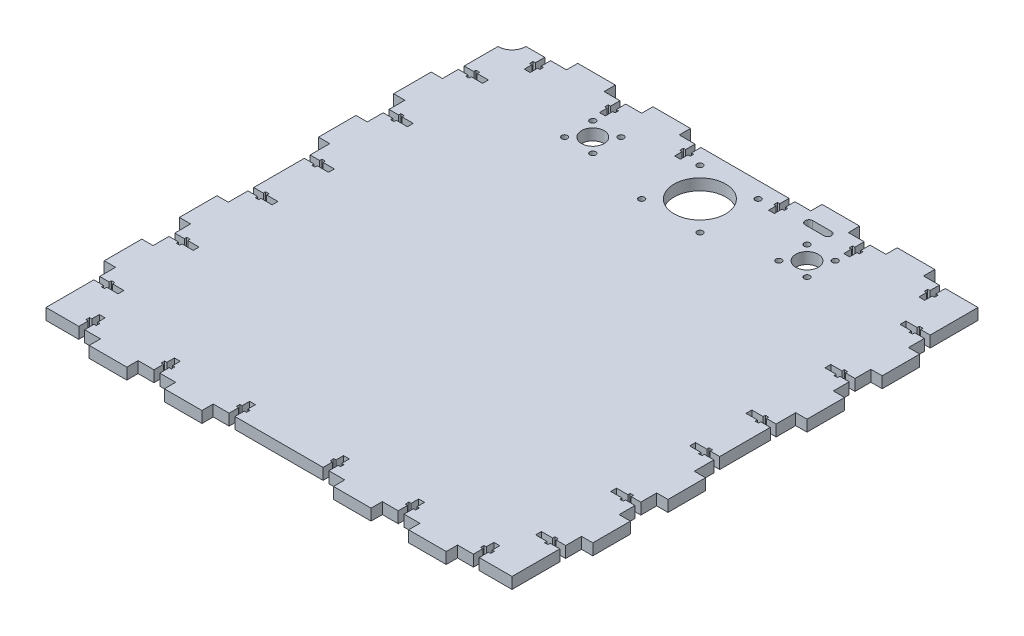
SolidWorks part; units mm, degrees
ref_plane "Front Plane" through (0, 0, 0) normal (0, 0, 1) x (1, 0, 0)
ref_plane "Top Plane" through (0, 0, 0) normal (0, 1, 0) x (1, 0, 0)
ref_plane "Right Plane" through (0, 0, 0) normal (1, 0, 0) x (0, 0, -1)
sketch "Sketch1" plane through (0, 0, 0) normal (0, 1, 0) x (1, 0, 0)
  line L0 (130, 260) -> (130, 0) construction
  line L1 (0, 0) -> (260, 0)
  line L2 (0, 0) -> (0, 260)
  line L3 (0, 260) -> (260, 260)
  line L4 (260, 0) -> (260, 260)
  line L5 (0, 260) -> (260, 260)
  line L6 (0, 260) -> (0, 254)
  line L7 (0, 254) -> (260, 254)
  line L8 (260, 260) -> (260, 254)
  line L9 (35, 260) -> (55, 260)
  line L10 (35, 260) -> (35, 254)
  line L11 (35, 254) -> (55, 254)
  line L12 (55, 260) -> (55, 254)
  line L13 (75, 254) -> (95, 254)
  line L14 (75, 254) -> (75, 260)
  line L15 (75, 260) -> (95, 260)
  line L16 (95, 254) -> (95, 260)
  line L17 (0, 130) -> (260, 130) construction
  line L18 (73, 230) -> (177.06, 230) construction
  line L19 (0, 260) -> (6, 260)
  line L20 (0, 260) -> (0, 0)
  line L21 (0, 0) -> (6, 0)
  line L22 (6, 260) -> (6, 0)
  line L23 (0, 217) -> (6, 217)
  line L24 (0, 217) -> (0, 197)
  line L25 (0, 197) -> (6, 197)
  line L26 (6, 217) -> (6, 197)
  line L27 (6, 177) -> (0, 177)
  line L28 (6, 177) -> (6, 157)
  line L29 (6, 157) -> (0, 157)
  line L30 (0, 177) -> (0, 157)
  line L31 (185, 260) -> (165, 260)
  line L32 (130, 214.5) -> (114.5, 214.5) construction
  line L34 (130, 245.5) -> (114.5, 245.5) construction
  line L35 (114.5, 214.5) -> (114.5, 245.5) construction
  line L36 (130, 230) -> (114.5, 245.5) construction
  line L37 (130, 230) -> (114.5, 214.5) construction
  line L38 (80.5, 222.5) -> (65.5, 222.5) construction
  line L39 (80.5, 222.5) -> (80.5, 237.5) construction
  line L40 (80.5, 237.5) -> (65.5, 237.5) construction
  line L41 (65.5, 222.5) -> (65.5, 237.5) construction
  line L42 (80.5, 222.5) -> (65.5, 237.5) construction
  line L43 (80.5, 237.5) -> (65.5, 222.5) construction
  line L44 (165, 254) -> (165, 260)
  line L45 (185, 254) -> (165, 254)
  line L46 (185, 254) -> (185, 260)
  line L47 (225, 254) -> (205, 254)
  line L48 (205, 260) -> (205, 254)
  line L49 (225, 260) -> (205, 260)
  line L50 (225, 260) -> (225, 254)
  line L51 (254, 157) -> (260, 157)
  line L52 (260, 177) -> (260, 157)
  line L53 (254, 177) -> (260, 177)
  line L54 (254, 177) -> (254, 157)
  line L55 (260, 197) -> (254, 197)
  line L56 (254, 217) -> (254, 197)
  line L57 (260, 217) -> (254, 217)
  line L58 (260, 217) -> (260, 197)
  line L59 (254, 83) -> (254, 103)
  line L60 (254, 83) -> (260, 83)
  line L61 (260, 83) -> (260, 103)
  line L62 (254, 103) -> (260, 103)
  line L63 (260, 43) -> (260, 63)
  line L64 (260, 43) -> (254, 43)
  line L65 (254, 43) -> (254, 63)
  line L66 (260, 63) -> (254, 63)
  line L67 (225, 0) -> (225, 6)
  line L68 (225, 0) -> (205, 0)
  line L69 (205, 0) -> (205, 6)
  line L70 (225, 6) -> (205, 6)
  line L71 (185, 6) -> (185, 0)
  line L72 (185, 6) -> (165, 6)
  line L73 (165, 6) -> (165, 0)
  line L74 (185, 0) -> (165, 0)
  line L75 (75, 0) -> (95, 0)
  line L76 (95, 6) -> (95, 0)
  line L77 (75, 6) -> (95, 6)
  line L78 (75, 6) -> (75, 0)
  line L79 (35, 6) -> (55, 6)
  line L80 (55, 0) -> (55, 6)
  line L81 (35, 0) -> (55, 0)
  line L82 (35, 0) -> (35, 6)
  line L83 (0, 63) -> (6, 63)
  line L84 (6, 43) -> (6, 63)
  line L85 (0, 43) -> (6, 43)
  line L86 (0, 43) -> (0, 63)
  line L87 (6, 103) -> (0, 103)
  line L88 (0, 83) -> (0, 103)
  line L89 (6, 83) -> (0, 83)
  line L90 (6, 83) -> (6, 103)
  line L91 (254, 260) -> (254, 0)
  line L92 (0, 6) -> (254, 6)
  circle A0 centre (73, 230) radius 6
  circle A1 centre (130, 230) radius 13.75
  circle A2 centre (65.5, 237.5) radius 1.55
  circle A3 centre (80.5, 237.5) radius 1.55
  circle A4 centre (80.5, 222.5) radius 1.55
  circle A5 centre (65.5, 222.5) radius 1.55
  circle A6 centre (114.5, 245.5) radius 1.55
  circle A7 centre (114.5, 214.5) radius 1.55
  circle A8 centre (145.5, 214.5) radius 1.55
  circle A9 centre (145.5, 245.5) radius 1.55
  circle A12 centre (187, 230) radius 6
  circle A15 centre (194.5, 237.5) radius 1.55
  circle A16 centre (194.5, 222.5) radius 1.55
  circle A17 centre (179.5, 222.5) radius 1.55
  circle A18 centre (179.5, 237.5) radius 1.55
  point P29 (3, 217)
  point P30 (3, 157)
  point P31 (3, 177)
  dimension "D13" = 12
  dimension "D14" = 27.5
  dimension "D16" = 15.5
  dimension "D22" = 3.1
  dimension "D25" = 15
  dimension "D26" = 15
  dimension "D27" = 10.6066
  dimension "D28" = 3.1
  dimension "D1" = 260
  dimension "D2" = 260
  dimension "D3" = 6
  dimension "D4" = 20
  dimension "D5" = 20
  dimension "D6" = 20
  dimension "D7" = 29
  dimension "D8" = 6
  dimension "D9" = 20
  dimension "D10" = 20
  dimension "D11" = 20
  dimension "D12" = 37
  dimension "D15" = 31
  dimension "D18" = 24
  dimension "D19" = 57
  dimension "D20" = 15
  dimension "D21" = 15
  dimension "D23" = 2
  dimension "D24" = 2
extrude "Boss-Extrude1" add sketch "Sketch1" along normal blind 6
sketch "Sketch2" plane through (0, 6, 0) normal (0, 1, 0) x (1, 0, 0)
  line L0 (6, 254) -> (35, 254) construction
  line L1 (23.45, 254) -> (26.55, 254)
  line L2 (23.45, 254) -> (23.45, 249)
  line L3 (23.45, 243.1) -> (26.55, 243.1)
  line L4 (26.55, 254) -> (26.55, 249)
  line L5 (103.45, 254) -> (106.55, 254)
  line L6 (26.55, 249) -> (27.75, 249)
  line L7 (22.25, 247.1) -> (23.45, 247.1)
  line L8 (22.25, 247.1) -> (22.25, 249)
  line L9 (22.25, 249) -> (23.45, 249)
  line L10 (27.75, 247.1) -> (27.75, 249)
  line L11 (23.45, 247.1) -> (23.45, 243.1)
  line L12 (26.55, 247.1) -> (27.75, 247.1)
  line L13 (26.55, 247.1) -> (26.55, 243.1)
  line L14 (45, 260) -> (45, 264.9812) construction
  line L15 (35, 260) -> (55, 260) construction
  line L28 (103.45, 254) -> (103.45, 249)
  line L29 (103.45, 243.1) -> (106.55, 243.1)
  line L30 (25, 243.1) -> (25, 260.914) construction
  line L31 (65, 243.1) -> (65, 260.914) construction
  line L32 (63.45, 247.1) -> (63.45, 243.1)
  line L33 (63.45, 247.1) -> (62.25, 247.1)
  line L34 (66.55, 247.1) -> (66.55, 243.1)
  line L35 (62.25, 247.1) -> (62.25, 249)
  line L36 (67.75, 249) -> (66.55, 249)
  line L37 (67.75, 247.1) -> (67.75, 249)
  line L38 (67.75, 247.1) -> (66.55, 247.1)
  line L39 (63.45, 249) -> (62.25, 249)
  line L40 (63.45, 254) -> (63.45, 249)
  line L41 (66.55, 243.1) -> (63.45, 243.1)
  line L42 (66.55, 254) -> (66.55, 249)
  line L43 (66.55, 254) -> (63.45, 254)
  line L44 (85, 260) -> (85, 268.4526) construction
  line L45 (75, 260) -> (95, 260) construction
  line L46 (106.55, 254) -> (106.55, 249)
  line L47 (106.55, 249) -> (107.75, 249)
  line L48 (102.25, 247.1) -> (103.45, 247.1)
  line L49 (102.25, 247.1) -> (102.25, 249)
  line L50 (102.25, 249) -> (103.45, 249)
  line L51 (107.75, 247.1) -> (107.75, 249)
  line L52 (103.45, 247.1) -> (103.45, 243.1)
  line L53 (106.55, 247.1) -> (107.75, 247.1)
  line L54 (106.55, 247.1) -> (106.55, 243.1)
  line L55 (130, 254) -> (130, 268.4526) construction
  line L56 (95, 254) -> (165, 254) construction
  line L62 (175, 260) -> (175, 268.4526) construction
  line L78 (195, 243.1) -> (195, 260.914) construction
  line L87 (235, 243.1) -> (235, 260.914) construction
  line L89 (215, 260) -> (215, 264.9812) construction
  line L98 (153.45, 247.1) -> (153.45, 243.1)
  line L99 (153.45, 247.1) -> (152.25, 247.1)
  line L100 (156.55, 247.1) -> (156.55, 243.1)
  line L101 (152.25, 247.1) -> (152.25, 249)
  line L102 (157.75, 249) -> (156.55, 249)
  line L103 (157.75, 247.1) -> (157.75, 249)
  line L104 (157.75, 247.1) -> (156.55, 247.1)
  line L105 (153.45, 249) -> (152.25, 249)
  line L106 (153.45, 254) -> (153.45, 249)
  line L107 (193.45, 254) -> (196.55, 254)
  line L108 (193.45, 254) -> (193.45, 249)
  line L109 (193.45, 243.1) -> (196.55, 243.1)
  line L110 (196.55, 254) -> (196.55, 249)
  line L111 (196.55, 249) -> (197.75, 249)
  line L112 (192.25, 247.1) -> (193.45, 247.1)
  line L113 (192.25, 247.1) -> (192.25, 249)
  line L114 (192.25, 249) -> (193.45, 249)
  line L115 (197.75, 247.1) -> (197.75, 249)
  line L116 (193.45, 247.1) -> (193.45, 243.1)
  line L117 (196.55, 247.1) -> (197.75, 247.1)
  line L118 (196.55, 247.1) -> (196.55, 243.1)
  line L119 (156.55, 243.1) -> (153.45, 243.1)
  line L120 (156.55, 254) -> (156.55, 249)
  line L121 (233.45, 247.1) -> (233.45, 243.1)
  line L122 (233.45, 247.1) -> (232.25, 247.1)
  line L123 (236.55, 247.1) -> (236.55, 243.1)
  line L124 (232.25, 247.1) -> (232.25, 249)
  line L125 (237.75, 249) -> (236.55, 249)
  line L126 (237.75, 247.1) -> (237.75, 249)
  line L127 (237.75, 247.1) -> (236.55, 247.1)
  line L128 (233.45, 249) -> (232.25, 249)
  line L129 (156.55, 254) -> (153.45, 254)
  line L130 (233.45, 254) -> (233.45, 249)
  line L131 (236.55, 243.1) -> (233.45, 243.1)
  line L132 (236.55, 254) -> (236.55, 249)
  line L133 (236.55, 254) -> (233.45, 254)
  line L134 (6, 130) -> (-18.5109, 130) construction
  line L135 (6, 157) -> (6, 103) construction
  line L136 (215, 0) -> (215, -4.9812) construction
  line L137 (235, 16.9) -> (235, -0.914) construction
  line L138 (195, 16.9) -> (195, -0.914) construction
  line L139 (175, 0) -> (175, -8.4526) construction
  line L140 (130, 6) -> (130, -8.4526) construction
  line L141 (85, 0) -> (85, -8.4526) construction
  line L142 (65, 16.9) -> (65, -0.914) construction
  line L143 (25, 16.9) -> (25, -0.914) construction
  line L144 (45, 0) -> (45, -4.9812) construction
  line L145 (236.55, 6) -> (233.45, 6)
  line L146 (236.55, 6) -> (236.55, 11)
  line L147 (236.55, 16.9) -> (233.45, 16.9)
  line L148 (233.45, 6) -> (233.45, 11)
  line L149 (156.55, 6) -> (153.45, 6)
  line L150 (233.45, 11) -> (232.25, 11)
  line L151 (237.75, 12.9) -> (236.55, 12.9)
  line L152 (237.75, 12.9) -> (237.75, 11)
  line L153 (237.75, 11) -> (236.55, 11)
  line L154 (232.25, 12.9) -> (232.25, 11)
  line L155 (236.55, 12.9) -> (236.55, 16.9)
  line L156 (233.45, 12.9) -> (232.25, 12.9)
  line L157 (233.45, 12.9) -> (233.45, 16.9)
  line L158 (156.55, 6) -> (156.55, 11)
  line L159 (156.55, 16.9) -> (153.45, 16.9)
  line L160 (196.55, 12.9) -> (196.55, 16.9)
  line L161 (196.55, 12.9) -> (197.75, 12.9)
  line L162 (193.45, 12.9) -> (193.45, 16.9)
  line L163 (197.75, 12.9) -> (197.75, 11)
  line L164 (192.25, 11) -> (193.45, 11)
  line L165 (192.25, 12.9) -> (192.25, 11)
  line L166 (192.25, 12.9) -> (193.45, 12.9)
  line L167 (196.55, 11) -> (197.75, 11)
  line L168 (196.55, 6) -> (196.55, 11)
  line L169 (193.45, 16.9) -> (196.55, 16.9)
  line L170 (193.45, 6) -> (193.45, 11)
  line L171 (193.45, 6) -> (196.55, 6)
  line L172 (153.45, 6) -> (153.45, 11)
  line L173 (153.45, 11) -> (152.25, 11)
  line L174 (157.75, 12.9) -> (156.55, 12.9)
  line L175 (157.75, 12.9) -> (157.75, 11)
  line L176 (157.75, 11) -> (156.55, 11)
  line L177 (152.25, 12.9) -> (152.25, 11)
  line L178 (156.55, 12.9) -> (156.55, 16.9)
  line L179 (153.45, 12.9) -> (152.25, 12.9)
  line L180 (153.45, 12.9) -> (153.45, 16.9)
  line L181 (106.55, 12.9) -> (106.55, 16.9)
  line L182 (106.55, 12.9) -> (107.75, 12.9)
  line L183 (103.45, 12.9) -> (103.45, 16.9)
  line L184 (107.75, 12.9) -> (107.75, 11)
  line L185 (102.25, 11) -> (103.45, 11)
  line L186 (102.25, 12.9) -> (102.25, 11)
  line L187 (102.25, 12.9) -> (103.45, 12.9)
  line L188 (106.55, 11) -> (107.75, 11)
  line L189 (106.55, 6) -> (106.55, 11)
  line L190 (66.55, 6) -> (63.45, 6)
  line L191 (66.55, 6) -> (66.55, 11)
  line L192 (66.55, 16.9) -> (63.45, 16.9)
  line L193 (63.45, 6) -> (63.45, 11)
  line L194 (63.45, 11) -> (62.25, 11)
  line L195 (67.75, 12.9) -> (66.55, 12.9)
  line L196 (67.75, 12.9) -> (67.75, 11)
  line L197 (67.75, 11) -> (66.55, 11)
  line L198 (62.25, 12.9) -> (62.25, 11)
  line L199 (66.55, 12.9) -> (66.55, 16.9)
  line L200 (63.45, 12.9) -> (62.25, 12.9)
  line L201 (63.45, 12.9) -> (63.45, 16.9)
  line L202 (103.45, 16.9) -> (106.55, 16.9)
  line L203 (103.45, 6) -> (103.45, 11)
  line L204 (26.55, 12.9) -> (26.55, 16.9)
  line L205 (26.55, 12.9) -> (27.75, 12.9)
  line L206 (23.45, 12.9) -> (23.45, 16.9)
  line L207 (27.75, 12.9) -> (27.75, 11)
  line L208 (22.25, 11) -> (23.45, 11)
  line L209 (22.25, 12.9) -> (22.25, 11)
  line L210 (22.25, 12.9) -> (23.45, 12.9)
  line L211 (26.55, 11) -> (27.75, 11)
  line L212 (103.45, 6) -> (106.55, 6)
  line L213 (26.55, 6) -> (26.55, 11)
  line L214 (23.45, 16.9) -> (26.55, 16.9)
  line L215 (23.45, 6) -> (23.45, 11)
  line L216 (23.45, 6) -> (26.55, 6)
  dimension "D1" = 3.1
  dimension "D2" = 20
  dimension "D3" = 1.9
  dimension "D4" = 5
  dimension "D5" = 4
  dimension "D6" = 5.5
  dimension "D7" = 1.2
extrude "Cut-Extrude1" cut sketch "Sketch2" against normal blind 10
sketch "Sketch3" plane through (0, 6, 0) normal (0, 1, 0) x (1, 0, 0)
  line L0 (6, 130) -> (279.3265, 130) construction
  line L1 (6, 157) -> (6, 103) construction
  line L2 (6, 254) -> (6, 217) construction
  line L3 (6, 228.55) -> (11.1, 228.55)
  line L4 (6, 228.55) -> (6, 225.45)
  line L5 (6, 225.45) -> (11.1, 225.45)
  line L6 (18.9, 228.55) -> (18.9, 225.45)
  line L7 (18.9, 187) -> (-3.2582, 187) construction
  line L8 (18.9, 115) -> (-3.7345, 115) construction
  line L9 (18.9, 227) -> (-6.1, 227) construction
  line L10 (12.9, 225.45) -> (12.9, 224.25)
  line L11 (12.9, 229.75) -> (11.1, 229.75)
  line L12 (12.9, 229.75) -> (12.9, 228.55)
  line L13 (12.9, 224.25) -> (11.1, 224.25)
  line L14 (11.1, 229.75) -> (11.1, 228.55)
  line L15 (12.9, 228.55) -> (18.9, 228.55)
  line L16 (11.1, 225.45) -> (11.1, 224.25)
  line L17 (12.9, 225.45) -> (18.9, 225.45)
  line L18 (12.9, 188.55) -> (18.9, 188.55)
  line L19 (11.1, 188.55) -> (11.1, 189.75)
  line L20 (12.9, 185.45) -> (18.9, 185.45)
  line L21 (11.1, 184.25) -> (11.1, 185.45)
  line L22 (12.9, 189.75) -> (11.1, 189.75)
  line L23 (12.9, 184.25) -> (12.9, 185.45)
  line L24 (12.9, 184.25) -> (11.1, 184.25)
  line L25 (12.9, 188.55) -> (12.9, 189.75)
  line L26 (18.9, 185.45) -> (18.9, 188.55)
  line L27 (6, 188.55) -> (11.1, 188.55)
  line L28 (6, 185.45) -> (6, 188.55)
  line L29 (6, 185.45) -> (11.1, 185.45)
  line L31 (6, 146.55) -> (11.1, 146.55)
  line L32 (6, 146.55) -> (6, 143.45)
  line L33 (6, 143.45) -> (11.1, 143.45)
  line L34 (18.9, 146.55) -> (18.9, 143.45)
  line L35 (12.9, 143.45) -> (12.9, 142.25)
  line L36 (12.9, 147.75) -> (11.1, 147.75)
  line L37 (12.9, 147.75) -> (12.9, 146.55)
  line L38 (12.9, 142.25) -> (11.1, 142.25)
  line L39 (11.1, 147.75) -> (11.1, 146.55)
  line L40 (12.9, 146.55) -> (18.9, 146.55)
  line L41 (11.1, 143.45) -> (11.1, 142.25)
  line L42 (12.9, 143.45) -> (18.9, 143.45)
  line L43 (18.9, 145) -> (-3.7345, 145) construction
  line L44 (18.9, 33) -> (-6.1, 33) construction
  line L45 (18.9, 73) -> (-3.2582, 73) construction
  line L46 (12.9, 116.55) -> (18.9, 116.55)
  line L47 (11.1, 116.55) -> (11.1, 117.75)
  line L48 (12.9, 113.45) -> (18.9, 113.45)
  line L49 (11.1, 112.25) -> (11.1, 113.45)
  line L50 (12.9, 117.75) -> (11.1, 117.75)
  line L51 (12.9, 112.25) -> (12.9, 113.45)
  line L52 (12.9, 112.25) -> (11.1, 112.25)
  line L53 (12.9, 116.55) -> (12.9, 117.75)
  line L54 (18.9, 113.45) -> (18.9, 116.55)
  line L55 (6, 116.55) -> (11.1, 116.55)
  line L56 (6, 113.45) -> (6, 116.55)
  line L57 (6, 113.45) -> (11.1, 113.45)
  line L58 (6, 74.55) -> (11.1, 74.55)
  line L59 (6, 74.55) -> (6, 71.45)
  line L60 (6, 71.45) -> (11.1, 71.45)
  line L61 (18.9, 74.55) -> (18.9, 71.45)
  line L62 (12.9, 71.45) -> (12.9, 70.25)
  line L63 (12.9, 75.75) -> (11.1, 75.75)
  line L64 (12.9, 75.75) -> (12.9, 74.55)
  line L65 (12.9, 70.25) -> (11.1, 70.25)
  line L66 (11.1, 75.75) -> (11.1, 74.55)
  line L67 (12.9, 74.55) -> (18.9, 74.55)
  line L68 (11.1, 71.45) -> (11.1, 70.25)
  line L69 (12.9, 71.45) -> (18.9, 71.45)
  line L70 (12.9, 34.55) -> (18.9, 34.55)
  line L71 (11.1, 34.55) -> (11.1, 35.75)
  line L72 (12.9, 31.45) -> (18.9, 31.45)
  line L73 (11.1, 30.25) -> (11.1, 31.45)
  line L74 (12.9, 35.75) -> (11.1, 35.75)
  line L75 (12.9, 30.25) -> (12.9, 31.45)
  line L76 (12.9, 30.25) -> (11.1, 30.25)
  line L77 (12.9, 34.55) -> (12.9, 35.75)
  line L78 (18.9, 31.45) -> (18.9, 34.55)
  line L79 (6, 34.55) -> (11.1, 34.55)
  line L80 (6, 31.45) -> (6, 34.55)
  line L81 (6, 31.45) -> (11.1, 31.45)
  line L82 (130, 254) -> (130, 6) construction
  line L83 (106.55, 254) -> (153.45, 254) construction
  line L84 (106.55, 6) -> (153.45, 6) construction
  line L85 (241.1, 73) -> (263.2582, 73) construction
  line L86 (241.1, 33) -> (266.1, 33) construction
  line L87 (241.1, 145) -> (263.7345, 145) construction
  line L88 (241.1, 227) -> (266.1, 227) construction
  line L89 (241.1, 115) -> (263.7345, 115) construction
  line L90 (241.1, 187) -> (263.2582, 187) construction
  line L91 (254, 31.45) -> (248.9, 31.45)
  line L92 (254, 31.45) -> (254, 34.55)
  line L93 (254, 34.55) -> (248.9, 34.55)
  line L94 (241.1, 31.45) -> (241.1, 34.55)
  line L95 (247.1, 34.55) -> (247.1, 35.75)
  line L96 (247.1, 30.25) -> (248.9, 30.25)
  line L97 (247.1, 30.25) -> (247.1, 31.45)
  line L98 (247.1, 35.75) -> (248.9, 35.75)
  line L99 (248.9, 30.25) -> (248.9, 31.45)
  line L100 (247.1, 31.45) -> (241.1, 31.45)
  line L101 (248.9, 34.55) -> (248.9, 35.75)
  line L102 (247.1, 34.55) -> (241.1, 34.55)
  line L103 (247.1, 71.45) -> (241.1, 71.45)
  line L104 (248.9, 71.45) -> (248.9, 70.25)
  line L105 (247.1, 74.55) -> (241.1, 74.55)
  line L106 (248.9, 75.75) -> (248.9, 74.55)
  line L107 (247.1, 70.25) -> (248.9, 70.25)
  line L108 (247.1, 75.75) -> (247.1, 74.55)
  line L109 (247.1, 75.75) -> (248.9, 75.75)
  line L110 (247.1, 71.45) -> (247.1, 70.25)
  line L111 (241.1, 74.55) -> (241.1, 71.45)
  line L112 (254, 71.45) -> (248.9, 71.45)
  line L113 (254, 74.55) -> (254, 71.45)
  line L114 (254, 74.55) -> (248.9, 74.55)
  line L115 (254, 113.45) -> (248.9, 113.45)
  line L116 (254, 113.45) -> (254, 116.55)
  line L117 (254, 116.55) -> (248.9, 116.55)
  line L118 (241.1, 113.45) -> (241.1, 116.55)
  line L119 (247.1, 116.55) -> (247.1, 117.75)
  line L120 (247.1, 112.25) -> (248.9, 112.25)
  line L121 (247.1, 112.25) -> (247.1, 113.45)
  line L122 (247.1, 117.75) -> (248.9, 117.75)
  line L123 (248.9, 112.25) -> (248.9, 113.45)
  line L124 (247.1, 113.45) -> (241.1, 113.45)
  line L125 (248.9, 116.55) -> (248.9, 117.75)
  line L126 (247.1, 116.55) -> (241.1, 116.55)
  line L127 (247.1, 143.45) -> (241.1, 143.45)
  line L128 (248.9, 143.45) -> (248.9, 142.25)
  line L129 (247.1, 146.55) -> (241.1, 146.55)
  line L130 (248.9, 147.75) -> (248.9, 146.55)
  line L131 (247.1, 142.25) -> (248.9, 142.25)
  line L132 (247.1, 147.75) -> (247.1, 146.55)
  line L133 (247.1, 147.75) -> (248.9, 147.75)
  line L134 (247.1, 143.45) -> (247.1, 142.25)
  line L135 (241.1, 146.55) -> (241.1, 143.45)
  line L136 (254, 143.45) -> (248.9, 143.45)
  line L137 (254, 146.55) -> (254, 143.45)
  line L138 (254, 146.55) -> (248.9, 146.55)
  line L139 (254, 185.45) -> (248.9, 185.45)
  line L140 (254, 185.45) -> (254, 188.55)
  line L141 (254, 188.55) -> (248.9, 188.55)
  line L142 (241.1, 185.45) -> (241.1, 188.55)
  line L143 (247.1, 188.55) -> (247.1, 189.75)
  line L144 (247.1, 184.25) -> (248.9, 184.25)
  line L145 (247.1, 184.25) -> (247.1, 185.45)
  line L146 (247.1, 189.75) -> (248.9, 189.75)
  line L147 (248.9, 184.25) -> (248.9, 185.45)
  line L148 (247.1, 185.45) -> (241.1, 185.45)
  line L149 (248.9, 188.55) -> (248.9, 189.75)
  line L150 (247.1, 188.55) -> (241.1, 188.55)
  line L151 (247.1, 225.45) -> (241.1, 225.45)
  line L152 (248.9, 225.45) -> (248.9, 224.25)
  line L153 (247.1, 228.55) -> (241.1, 228.55)
  line L154 (248.9, 229.75) -> (248.9, 228.55)
  line L155 (247.1, 224.25) -> (248.9, 224.25)
  line L156 (247.1, 229.75) -> (247.1, 228.55)
  line L157 (247.1, 229.75) -> (248.9, 229.75)
  line L158 (247.1, 225.45) -> (247.1, 224.25)
  line L159 (241.1, 228.55) -> (241.1, 225.45)
  line L160 (254, 225.45) -> (248.9, 225.45)
  line L161 (254, 228.55) -> (254, 225.45)
  line L162 (254, 228.55) -> (248.9, 228.55)
  dimension "D1" = 12.9
  dimension "D2" = 3.1
  dimension "D3" = 5.5
  dimension "D4" = 2.75
  dimension "D5" = 1.8
  dimension "D6" = 6
  dimension "D7" = 42
  dimension "D8" = 40
  dimension "D9" = 15
extrude "Cut-Extrude2" cut sketch "Sketch3" against normal blind 10
sketch "Sketch4" plane through (0, 6, 0) normal (0, 1, 0) x (1, 0, 0)
  line L0 (170, 248.0484) -> (180, 248.0484) construction
  line L1 (170, 250.0484) -> (180, 250.0484)
  line L2 (170, 246.0484) -> (180, 246.0484)
  line L3 (165, 254) -> (165, 260) construction
  line L4 (130, 254) -> (130, 267.0209) construction
  line L5 (106.55, 254) -> (153.45, 254) construction
  line L7 (130, 267.0209) -> (130, 226.89) construction
  arc A0 (170, 250.0484) -> (170, 246.0484) centre (170, 248.0484) ccw
  arc A1 (180, 246.0484) -> (180, 250.0484) centre (180, 248.0484) ccw
  circle A4 centre (6, 254) radius 7.5
  point P2 (175, 248.0484)
  dimension "D4" = 15
  dimension "D1" = 10
  dimension "D2" = 10
  dimension "D3" = 2
extrude "Cut-Extrude3" cut sketch "Sketch4" against normal blind 10
equation "\"`0\"=12.2695"
